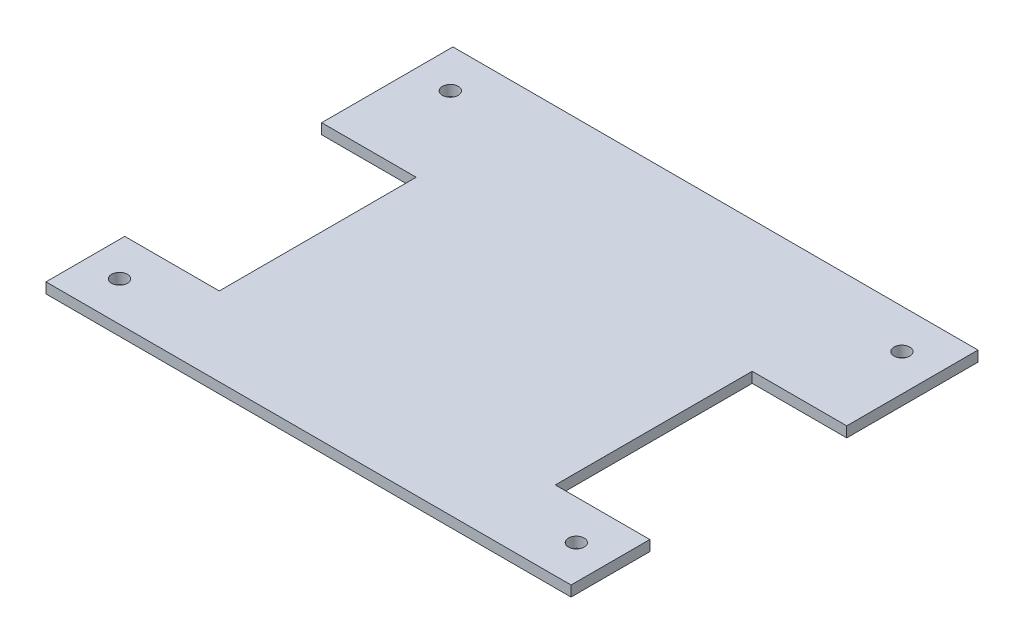
SolidWorks part; units mm, degrees
ref_plane "Front Plane" through (0, 0, 0) normal (0, 0, 1) x (1, 0, 0)
ref_plane "Top Plane" through (0, 0, 0) normal (0, 1, 0) x (1, 0, 0)
ref_plane "Right Plane" through (0, 0, 0) normal (1, 0, 0) x (0, 0, -1)
sketch "Sketch1" plane through (0, 0, 0) normal (0, 1, 0) x (1, 0, 0)
  line L0 (-128.4173, -2.6724) -> (-92.4173, -2.6724)
  line L2 (71.5827, 47.3276) -> (71.5827, -2.6724)
  line L3 (71.5827, -107.6724) -> (-128.4173, -107.6724)
  line L4 (-128.4173, 47.3276) -> (-128.4173, -2.6724)
  line L5 (-128.4173, 47.3276) -> (71.5827, 47.3276)
  line L7 (-92.4173, -2.6724) -> (-92.4173, -77.6724)
  line L8 (-92.4173, -77.6724) -> (-128.4173, -77.6724)
  line L9 (-28.4173, -17.5953) -> (-28.4173, -107.6724) construction
  line L10 (35.5827, -77.6724) -> (71.5827, -77.6724)
  line L11 (35.5827, -2.6724) -> (35.5827, -77.6724)
  line L12 (71.5827, -2.6724) -> (35.5827, -2.6724)
  line L13 (-128.4173, -77.6724) -> (-128.4173, -107.6724)
  line L14 (71.5827, -77.6724) -> (71.5827, -107.6724)
  circle A2 centre (-115.4173, -92.6724) radius 3
  circle A3 centre (58.5827, -92.6724) radius 3
  circle A4 centre (-114.4173, 32.3276) radius 3
  circle A5 centre (57.5827, 32.3276) radius 3
  point P0 (0, 0)
  point P21 (-118.4173, 30.6692)
  point P22 (0, 0)
  dimension "D9" = 13
  dimension "D7" = 15
  dimension "D1" = 200
  dimension "D2" = 75
  dimension "D3" = 36
  dimension "D4" = 75
  dimension "D5" = 30
  dimension "D6" = 50
  dimension "D8" = 50
  dimension "D10" = 14
  dimension "D11" = 35
extrude "Boss-Extrude1" add sketch "Sketch1" along normal blind 4
